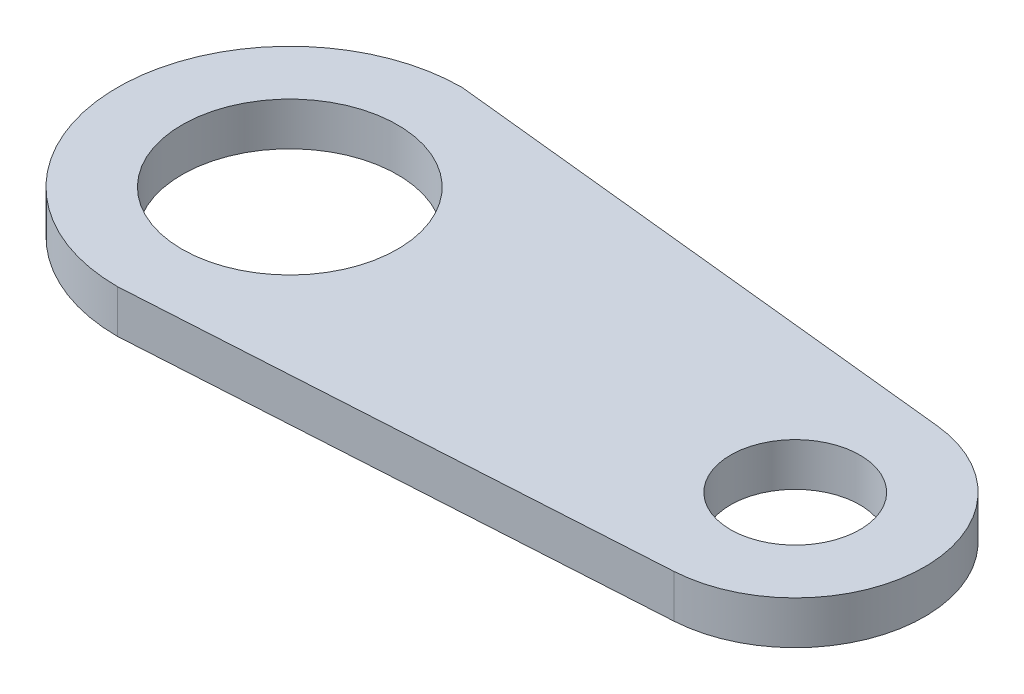
SolidWorks part; units mm, degrees
ref_plane "Front Plane" through (0, 0, 0) normal (0, 0, 1) x (1, 0, 0)
ref_plane "Top Plane" through (0, 0, 0) normal (0, 1, 0) x (1, 0, 0)
ref_plane "Right Plane" through (0, 0, 0) normal (1, 0, 0) x (0, 0, -1)
sketch "Sketch1" plane through (0, 0, 0) normal (0, 1, 0) x (1, 0, 0)
  line L0 (0, 20) -> (61.5451, 13.5626)
  line L1 (0, -20) -> (60.8875, -16.3288)
  arc A0 (0, 20) -> (2.4031, -19.8551) centre (0, 0) ccw
  arc A1 (60.8875, -16.3288) -> (61.5451, 13.5626) centre (59.9847, -1.356) ccw
  dimension "D1" = 20
  dimension "D2" = 15
  dimension "D3" = 60
extrude "Boss-Extrude1" add sketch "Sketch1" along normal blind 5 contours L1 A1 L0 A0
sketch "Sketch2" plane through (0, 5, 0) normal (0, 1, 0) x (1, 0, 0)
  circle A0 centre (0, 0) radius 12.5
  circle A1 centre (59.9847, -1.356) radius 7.5
  dimension "D1" = 25
  dimension "D2" = 15
extrude "Cut-Extrude1" cut sketch "Sketch2" against normal blind 10
